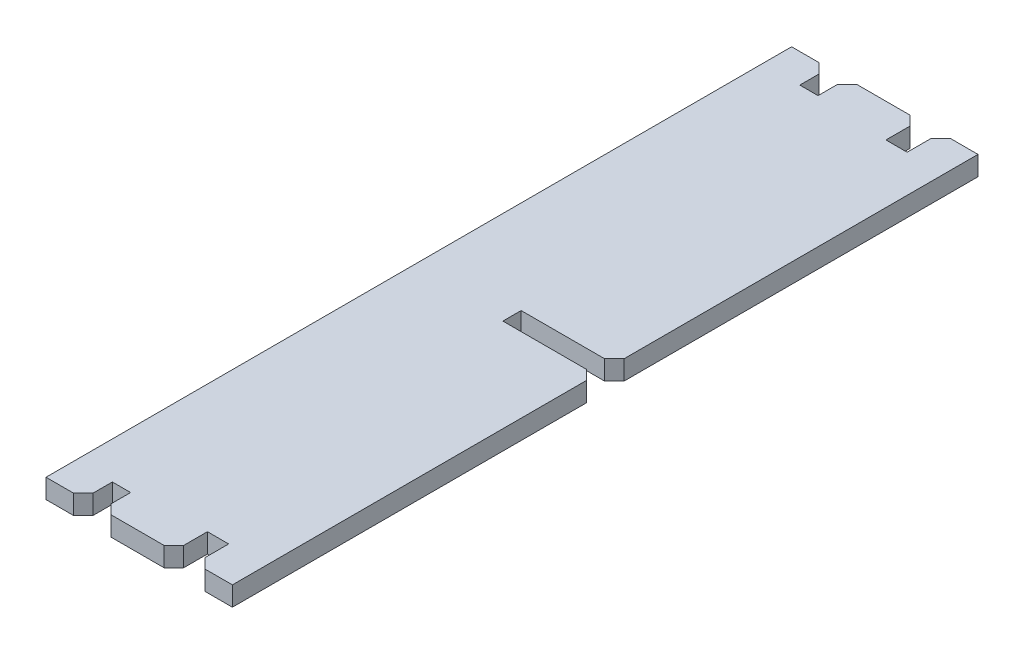
SolidWorks part; units mm, degrees
ref_plane "Front Plane" through (0, 0, 0) normal (0, 0, 1) x (1, 0, 0)
ref_plane "Top Plane" through (0, 0, 0) normal (0, 1, 0) x (1, 0, 0)
ref_plane "Right Plane" through (0, 0, 0) normal (1, 0, 0) x (0, 0, -1)
sketch "Sketch1" plane through (0, 0, 0) normal (0, 1, 0) x (1, 0, 0)
  line L1 (0, 0) -> (50, 0)
  line L2 (0, 0) -> (0, 200)
  line L3 (0, 200) -> (50, 200)
  line L4 (50, 0) -> (50, 200)
  dimension "D1" = 50
  dimension "D2" = 200
extrude "Boss-Extrude1" add sketch "Sketch1" along normal blind 5.2
sketch "Sketch2" plane through (0, 5.2, 0) normal (0, 1, 0) x (1, 0, 0)
  line L0 (50, 200) -> (0, 200) construction
  line L1 (10, 200) -> (14.9, 200)
  line L2 (10, 200) -> (10, 192.2)
  line L3 (10, 192.2) -> (14.9, 192.2)
  line L4 (14.9, 200) -> (14.9, 192.2)
  line L5 (0, 200) -> (0, 0) construction
  line L6 (34.3, 200) -> (40, 200)
  line L7 (50, 0) -> (50, 200) construction
  line L8 (50, 102.45) -> (25, 102.45)
  line L9 (50, 102.45) -> (50, 97.55)
  line L10 (50, 97.55) -> (25, 97.55)
  line L11 (25, 102.45) -> (25, 97.55)
  line L12 (34.3, 200) -> (34.3, 191)
  line L17 (0, 0) -> (50, 0) construction
  line L18 (10, 0) -> (14.9, 0)
  line L19 (10, 0) -> (10, 7.8)
  line L20 (10, 7.8) -> (14.9, 7.8)
  line L21 (14.9, 0) -> (14.9, 7.8)
  line L22 (34.3, 191) -> (40, 191)
  line L23 (40, 200) -> (40, 191)
  line L24 (34.3, 9) -> (40, 9)
  line L25 (34.3, 9) -> (34.3, 0)
  line L26 (34.3, 0) -> (40, 0)
  line L27 (40, 9) -> (40, 0)
  point P18 (37.15, 200)
  point P27 (50, 100)
  point P28 (50, 100)
  dimension "D1" = 7.8
  dimension "D2" = 4.9
  dimension "D3" = 4.9
  dimension "D4" = 25
  dimension "D5" = 10
  dimension "D6" = 5.7
  dimension "D7" = 10
  dimension "D8" = 5.7
  dimension "D9" = 10
extrude "Cut-Extrude1" cut sketch "Sketch2" against normal blind 5.2
chamfer "Chamfer2" distance 2.6 angle 45 10 edges at (10, 2.6, -200) (14.9, 2.6, -200) (10, 2.6, 0) (14.9, 2.6, 0) (50, 2.6, -97.55) (50, 2.6, -102.45) (34.3, 2.6, -200) (40, 2.6, -200) (34.3, 2.6, 0) (40, 2.6, 0)
equation "\"thick\"= 5.2'board thickness"
equation "\"fit\"= 0.3mm'fit adjustment"
equation "\"depth\"= \"thick\" * 1.5'cut depth"
equation "\"chamfer\"= \"thick\" / 2'fillet radius"
equation "\"width\"= \"thick\" - \"fit\"'cut width"
equation "\"gap\"= \"depth\" * 2'cut gap"
equation "\"curv\"= \"gap\" * 2'curvature radius"
equation "\"D1@Boss-Extrude1\"=\"thick\""
equation "\"D1@Sketch2\"=\"depth\""
equation "\"D2@Sketch2\"=\"width\""
equation "\"D1@Cut-Extrude1\"=\"thick\""
equation "\"D1@Chamfer2\"=\"chamfer\""
equation "\"D3@Sketch2\"=\"width\""
